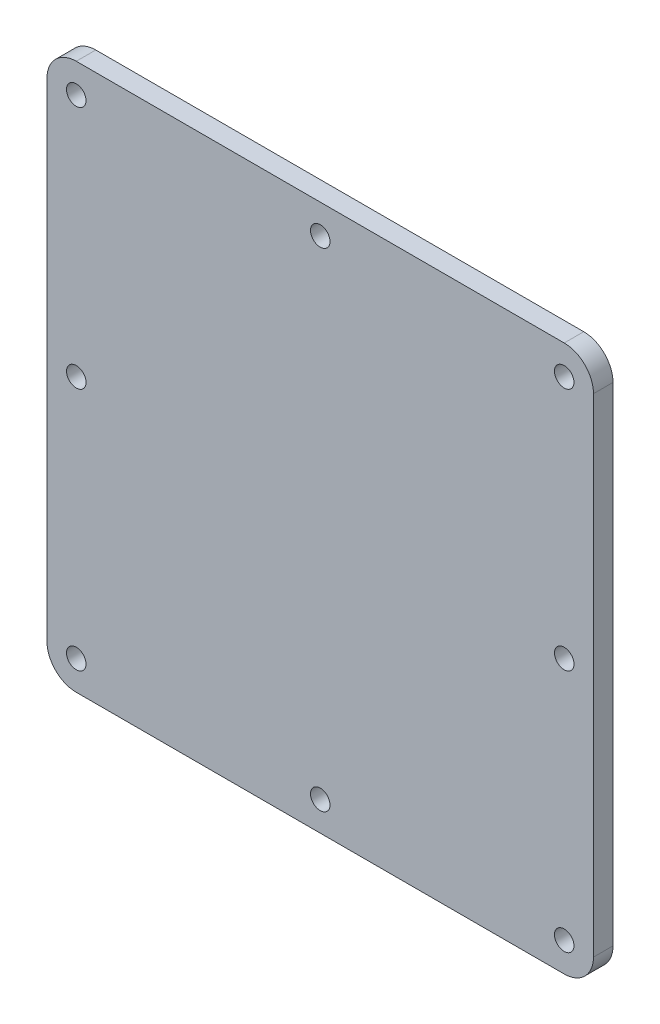
SolidWorks part; units mm, degrees
ref_plane "Front Plane" through (0, 0, 0) normal (0, 0, 1) x (1, 0, 0)
ref_plane "Top Plane" through (0, 0, 0) normal (0, 1, 0) x (1, 0, 0)
ref_plane "Right Plane" through (0, 0, 0) normal (1, 0, 0) x (0, 0, -1)
sketch "Sketch2" plane through (0, 0, 0) normal (0, 0, 1) x (1, 0, 0)
  line L0 (-125, 125) -> (125, 125) construction
  line L1 (-125, 140) -> (125, 140)
  line L2 (-140, 125) -> (-140, -125)
  line L3 (-125, -140) -> (125, -140)
  line L4 (140, 125) -> (140, -125)
  line L5 (-140, 140) -> (140, -140) construction
  line L6 (-140, -140) -> (140, 140) construction
  line L7 (125, 125) -> (125, -125) construction
  line L8 (125, -125) -> (-125, -125) construction
  line L9 (-125, -125) -> (-125, 125) construction
  arc A0 (-140, -125) -> (-125, -140) centre (-125, -125) ccw
  arc A1 (125, -140) -> (140, -125) centre (125, -125) ccw
  arc A2 (125, 140) -> (140, 125) centre (125, 125) cw
  arc A3 (-125, 140) -> (-140, 125) centre (-125, 125) ccw
  circle A4 centre (-125, 125) radius 5
  circle A5 centre (0, 125) radius 5
  circle A6 centre (125, 125) radius 5
  circle A14 centre (125, 0) radius 5
  circle A15 centre (-125, 0) radius 5
  circle A16 centre (-125, -125) radius 5
  circle A17 centre (0, -125) radius 5
  circle A18 centre (125, -125) radius 5
  point P0 (0, 0)
  dimension "D3" = 15
  dimension "D4" = 10
  dimension "D5" = 10
  dimension "D6" = 10
  dimension "D8" = 10
  dimension "D9" = 10
  dimension "D10" = 10
  dimension "D11" = 10
  dimension "D1" = 280
  dimension "D2" = 280
extrude "Boss-Extrude1" add sketch "Sketch2" along normal blind 10
